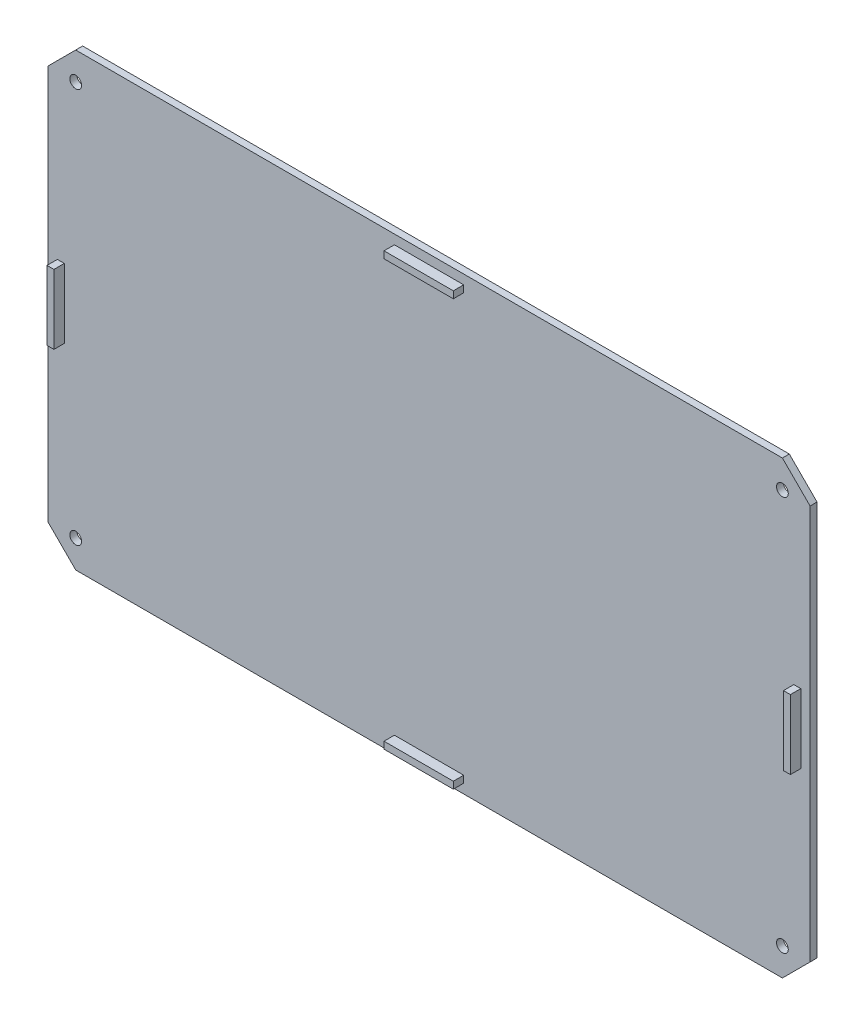
SolidWorks part; units mm, degrees
ref_plane "Front Plane" through (0, 0, 0) normal (0, 0, 1) x (1, 0, 0)
ref_plane "Top Plane" through (0, 0, 0) normal (0, 1, 0) x (1, 0, 0)
ref_plane "Right Plane" through (0, 0, 0) normal (1, 0, 0) x (0, 0, -1)
sketch "Sketch1" plane through (0, 0, 0) normal (0, 0, 1) x (1, 0, 0)
  line L0 (-102, -65) -> (102, -65)
  line L1 (102, -65) -> (110, -57)
  line L2 (110, -57) -> (110, 57)
  line L3 (110, 57) -> (102, 65)
  line L4 (102, 65) -> (-102, 65)
  line L5 (-102, 65) -> (-110, 57)
  line L6 (-110, 57) -> (-110, -57)
  line L7 (-110, -57) -> (-102, -65)
extrude "Faceted_Removable_Lid" add sketch "Sketch1" along normal blind 2 from offset 0
sketch "Sketch2" plane through (0, 0, 0) normal (0, 0, 1) x (1, 0, 0)
  line L1 (-10, -62.3) -> (10, -62.3)
  line L2 (-10, -62.3) -> (-10, -60.3)
  line L3 (-10, -60.3) -> (10, -60.3)
  line L4 (10, -62.3) -> (10, -60.3)
extrude "Side_Locator_-1" add sketch "Sketch2" along normal blind 3 from offset 2
sketch "Sketch3" plane through (0, 0, 0) normal (0, 0, 1) x (1, 0, 0)
  line L1 (-107.3, -10) -> (-105.3, -10)
  line L2 (-107.3, -10) -> (-107.3, 10)
  line L3 (-107.3, 10) -> (-105.3, 10)
  line L4 (-105.3, -10) -> (-105.3, 10)
extrude "End_Locator_-1" add sketch "Sketch3" along normal blind 3 from offset 2
sketch "Sketch4" plane through (0, 0, 0) normal (0, 0, 1) x (1, 0, 0)
  line L1 (-10, 60.3) -> (10, 60.3)
  line L2 (-10, 60.3) -> (-10, 62.3)
  line L3 (-10, 62.3) -> (10, 62.3)
  line L4 (10, 60.3) -> (10, 62.3)
extrude "Side_Locator_1" add sketch "Sketch4" along normal blind 3 from offset 2
sketch "Sketch5" plane through (0, 0, 0) normal (0, 0, 1) x (1, 0, 0)
  line L1 (105.3, -10) -> (107.3, -10)
  line L2 (105.3, -10) -> (105.3, 10)
  line L3 (105.3, 10) -> (107.3, 10)
  line L4 (107.3, -10) -> (107.3, 10)
extrude "End_Locator_1" add sketch "Sketch5" along normal blind 3 from offset 2
sketch "Sketch6" plane through (0, 0, 0) normal (0, 0, 1) x (1, 0, 0)
  circle A0 centre (-102, -57) radius 1.7
extrude "M3_Lid_Clearance_-1_-1" cut sketch "Sketch6" along normal blind 2.2 from offset 0.1
sketch "Sketch7" plane through (0, 0, 0) normal (0, 0, 1) x (1, 0, 0)
  circle A0 centre (-102, 57) radius 1.7
extrude "M3_Lid_Clearance_-1_1" cut sketch "Sketch7" along normal blind 2.2 from offset 0.1
sketch "Sketch8" plane through (0, 0, 0) normal (0, 0, 1) x (1, 0, 0)
  circle A0 centre (102, -57) radius 1.7
extrude "M3_Lid_Clearance_1_-1" cut sketch "Sketch8" along normal blind 2.2 from offset 0.1
sketch "Sketch9" plane through (0, 0, 0) normal (0, 0, 1) x (1, 0, 0)
  circle A0 centre (102, 57) radius 1.7
extrude "M3_Lid_Clearance_1_1" cut sketch "Sketch9" along normal blind 2.2 from offset 0.1
